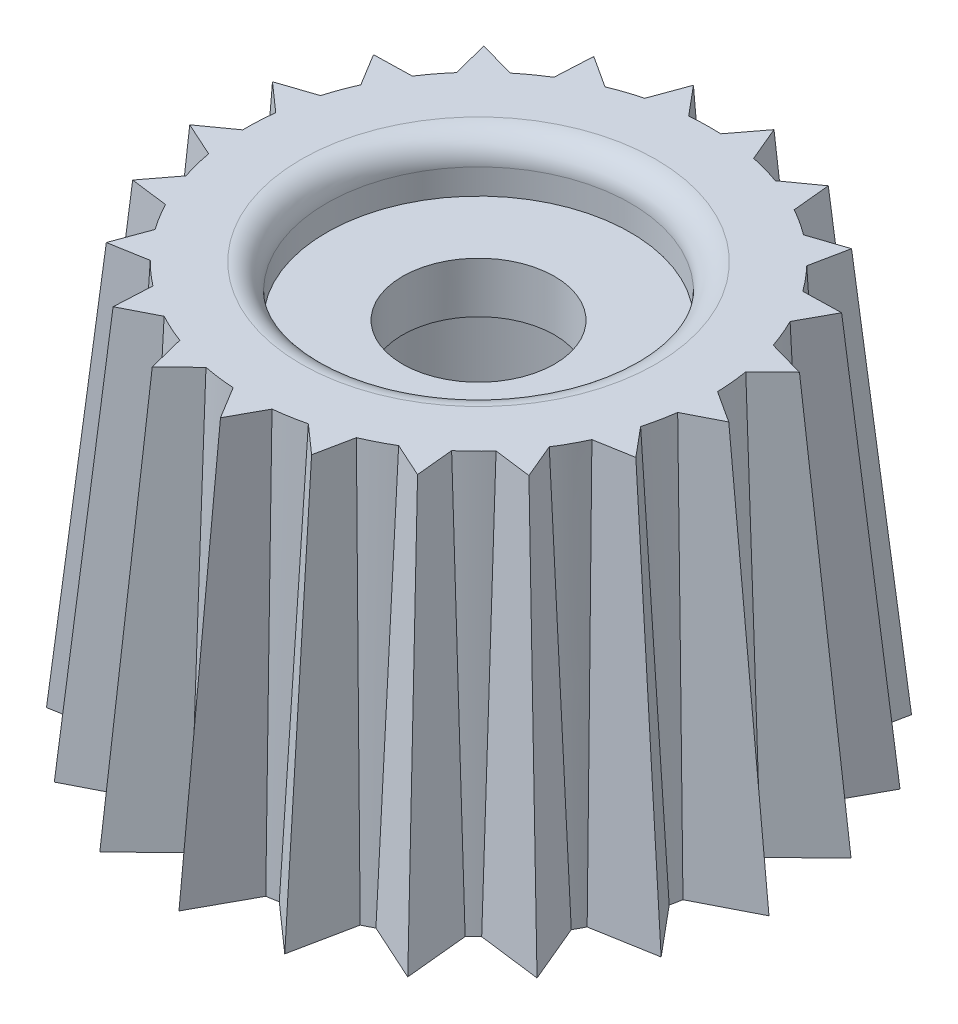
SolidWorks part; units mm, degrees
ref_plane "Front Plane" through (0, 0, 0) normal (0, 0, 1) x (1, 0, 0)
ref_plane "Top Plane" through (0, 0, 0) normal (0, 1, 0) x (1, 0, 0)
ref_plane "Right Plane" through (0, 0, 0) normal (1, 0, 0) x (0, 0, -1)
sketch "Sketch1" plane through (0, 0, 0) normal (0, 1, 0) x (1, 0, 0)
  line L0 (0, 5) -> (0.7637, 6.0044)
  line L1 (0.7637, 6.0044) -> (1.2517, 4.8408)
  line L3 (1.4738, 4.7779) -> (2.4996, 5.5125)
  line L4 (2.4996, 5.5125) -> (2.623, 4.2568)
  line L6 (2.8166, 4.1312) -> (4.0134, 4.5308)
  line L7 (4.0134, 4.5308) -> (3.7611, 3.2945)
  line L9 (3.9092, 3.1174) -> (5.1706, 3.1466)
  line L10 (5.1706, 3.1466) -> (4.5651, 2.0395)
  line L12 (4.6544, 1.8267) -> (5.8684, 1.4827)
  line L13 (5.8684, 1.4827) -> (4.9635, 0.6033)
  line L15 (4.986, 0.3737) -> (6.0447, -0.3129)
  line L16 (6.0447, -0.3129) -> (4.9208, -0.8865)
  line L18 (4.8746, -1.1126) -> (5.6839, -2.0807)
  line L19 (5.6839, -2.0807) -> (4.4409, -2.2975)
  line L21 (4.3301, -2.5) -> (4.8181, -3.6636)
  line L22 (4.8181, -3.6636) -> (3.5664, -3.5044)
  line L24 (3.4009, -3.6653) -> (3.5242, -4.921)
  line L25 (3.5242, -4.921) -> (2.375, -4.3999)
  line L27 (2.1694, -4.5048) -> (1.9171, -5.7412)
  line L28 (1.9171, -5.7412) -> (0.9726, -4.9045)
  line L30 (0.7452, -4.9442) -> (0.1397, -6.0512)
  line L31 (0.1397, -6.0512) -> (-0.5163, -4.9733)
  line L33 (-0.7452, -4.9442) -> (-1.6501, -5.8235)
  line L34 (-1.6501, -5.8235) -> (-1.9592, -4.6002)
  line L36 (-2.1694, -4.5048) -> (-3.2933, -5.0784)
  line L37 (-3.2933, -5.0784) -> (-3.2281, -3.8183)
  line L39 (-3.4009, -3.6653) -> (-4.6439, -3.8821)
  line L40 (-4.6439, -3.8821) -> (-4.2101, -2.6972)
  line L42 (-4.3301, -2.5) -> (-5.5818, -2.3408)
  line L43 (-5.5818, -2.3408) -> (-4.8181, -1.3364)
  line L45 (-4.8746, -1.1126) -> (-6.0238, -0.5915)
  line L46 (-6.0238, -0.5915) -> (-4.998, 0.1432)
  line L48 (-4.986, 0.3737) -> (-5.9305, 1.2103)
  line L49 (-5.9305, 1.2103) -> (-4.7337, 1.61)
  line L51 (-4.6544, 1.8267) -> (-5.3103, 2.9046)
  line L52 (-5.3103, 2.9046) -> (-4.0489, 2.9337)
  line L54 (-3.9092, 3.1174) -> (-4.2183, 4.3408)
  line L55 (-4.2183, 4.3408) -> (-3.0042, 3.9968)
  line L57 (-2.8166, 4.1312) -> (-2.7514, 5.3913)
  line L58 (-2.7514, 5.3913) -> (-1.6927, 4.7048)
  line L60 (-1.4738, 4.7779) -> (-1.04, 5.9628)
  line L61 (-1.04, 5.9628) -> (-0.2307, 4.9947)
  arc A0 (3.4009, -3.6653) -> (3.5664, -3.5044) centre (0, 0) ccw
  arc A1 (4.3301, -2.5) -> (4.4409, -2.2975) centre (0, 0) ccw
  arc A2 (4.8746, -1.1126) -> (4.9208, -0.8865) centre (0, 0) ccw
  arc A3 (4.986, 0.3737) -> (4.9635, 0.6033) centre (0, 0) ccw
  arc A4 (4.6544, 1.8267) -> (4.5651, 2.0395) centre (0, 0) ccw
  arc A5 (3.9092, 3.1174) -> (3.7611, 3.2945) centre (0, 0) ccw
  arc A6 (2.8166, 4.1312) -> (2.623, 4.2568) centre (0, 0) ccw
  arc A7 (1.4738, 4.7779) -> (1.2517, 4.8408) centre (0, 0) ccw
  arc A8 (0, 5) -> (-0.2307, 4.9947) centre (0, 0) ccw
  arc A9 (-1.4738, 4.7779) -> (-1.6927, 4.7048) centre (0, 0) ccw
  arc A10 (-2.8166, 4.1312) -> (-3.0042, 3.9968) centre (0, 0) ccw
  arc A11 (-3.9092, 3.1174) -> (-4.0489, 2.9337) centre (0, 0) ccw
  arc A12 (-4.6544, 1.8267) -> (-4.7337, 1.61) centre (0, 0) ccw
  arc A13 (-4.986, 0.3737) -> (-4.998, 0.1432) centre (0, 0) ccw
  arc A14 (-4.8746, -1.1126) -> (-4.8181, -1.3364) centre (0, 0) ccw
  arc A15 (-4.3301, -2.5) -> (-4.2101, -2.6972) centre (0, 0) ccw
  arc A16 (-3.4009, -3.6653) -> (-3.2281, -3.8183) centre (0, 0) ccw
  arc A17 (-2.1694, -4.5048) -> (-1.9592, -4.6002) centre (0, 0) ccw
  arc A18 (-0.7452, -4.9442) -> (-0.5163, -4.9733) centre (0, 0) ccw
  arc A19 (2.1694, -4.5048) -> (2.375, -4.3999) centre (0, 0) ccw
  arc A20 (0.7452, -4.9442) -> (0.9726, -4.9045) centre (0, 0) ccw
  point P69 (0, 0)
  dimension "D1" = 10
  dimension "D2" = 60
  dimension "D3" = 1.2363
  dimension "D5" = 21
extrude "Boss-Extrude1" add sketch "Sketch1" along normal blind 8 draft 3
sketch "Sketch2" plane through (0, 0, 0) normal (0, -1, 0) x (1, 0, 0)
  circle A0 centre (0, 0) radius 3
  dimension "D1" = 6
extrude "Cut-Extrude1" cut sketch "Sketch2" against normal blind 6
sketch "Sketch3" plane through (0, 6, 0) normal (0, -1, 0) x (1, 0, 0)
  circle A0 centre (0, 0) radius 1.5
  dimension "D1" = 3
extrude "Cut-Extrude2" cut sketch "Sketch3" against normal blind 6
fillet "Fillet3" radius 0.5 1 edges at (0, 6, -3)
sketch "Sketch4" plane through (0, 8, 0) normal (0, 1, 0) x (1, 0, 0)
  circle A0 centre (0, 0) radius 3
  dimension "D1" = 6
extrude "Cut-Extrude3" cut sketch "Sketch4" against normal blind 1
fillet "Fillet4" radius 0.5 1 edges at (0, 8, 3)
